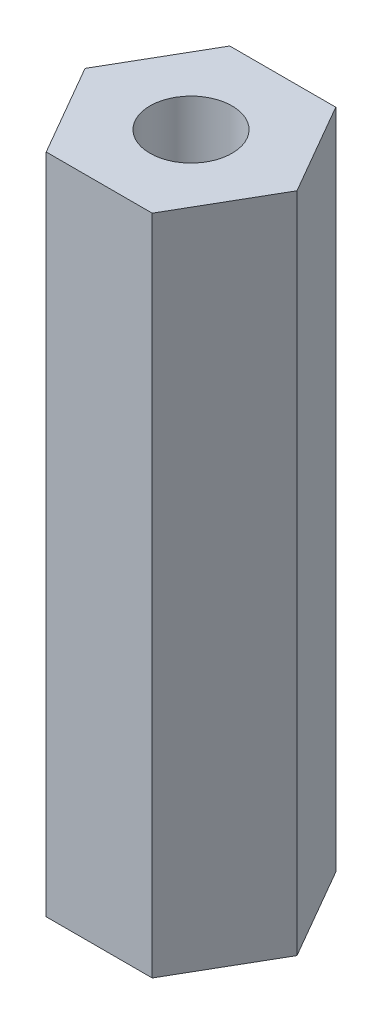
SolidWorks part; units mm, degrees
ref_plane "前基準面" through (0, 0, 0) normal (0, 0, 1) x (1, 0, 0)
ref_plane "上基準面" through (0, 0, 0) normal (0, 1, 0) x (1, 0, 0)
ref_plane "右基準面" through (0, 0, 0) normal (1, 0, 0) x (0, 0, -1)
sketch "草圖1" plane through (0, 0, 0) normal (0, 1, 0) x (1, 0, 0)
  line L1 (2, 3.4641) -> (-2, 3.4641)
  line L2 (-2, 3.4641) -> (-4, 0)
  line L3 (-4, 0) -> (-2, -3.4641)
  line L4 (-2, -3.4641) -> (2, -3.4641)
  line L5 (2, -3.4641) -> (4, 0)
  line L6 (4, 0) -> (2, 3.4641)
  circle A0 centre (0, 0) radius 3.4641 construction
  circle A1 centre (0, 0) radius 1.55
  dimension "D1" = 3.1
  dimension "D2" = 4
extrude "填料-伸長1" add sketch "草圖1" along normal blind 25 contours A1 | L1 L2 L3 L4 L5 L6
